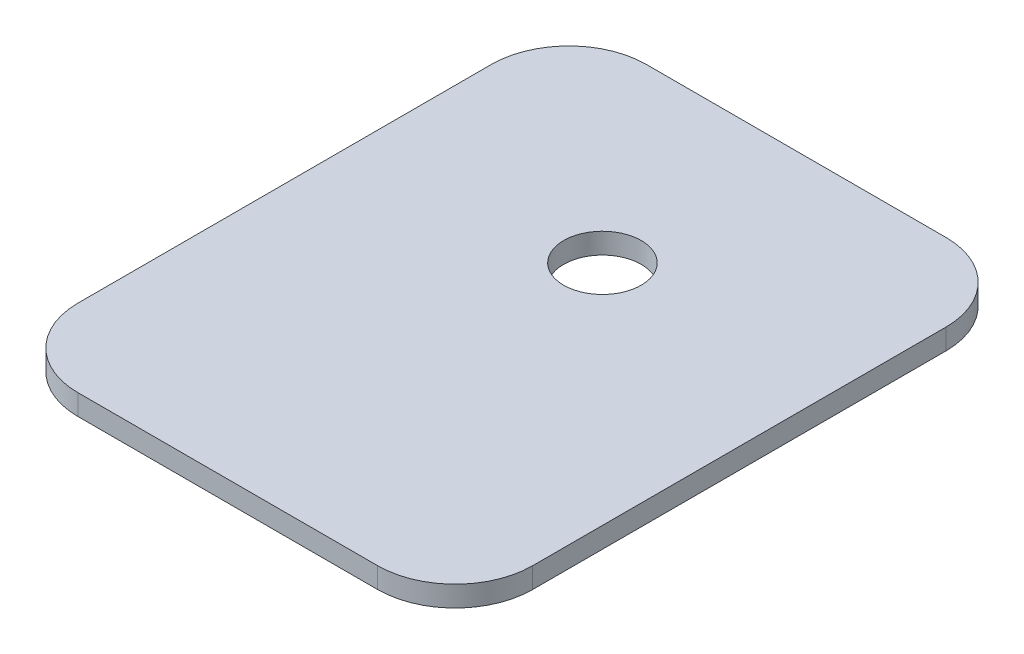
SolidWorks part; units mm, degrees
ref_plane "Front Plane" through (0, 0, 0) normal (0, 0, 1) x (1, 0, 0)
ref_plane "Top Plane" through (0, 0, 0) normal (0, 1, 0) x (1, 0, 0)
ref_plane "Right Plane" through (0, 0, 0) normal (1, 0, 0) x (0, 0, -1)
sketch "Sketch1" plane through (0, 0, 0) normal (0, 1, 0) x (1, 0, 0)
  line L1 (-17.6, -22) -> (17.6, -22)
  line L2 (-17.6, -22) -> (-17.6, 22)
  line L3 (-17.6, 22) -> (17.6, 22)
  line L4 (17.6, -22) -> (17.6, 22)
  line L5 (-17.6, -22) -> (17.6, 22) construction
  line L6 (-17.6, 22) -> (17.6, -22) construction
  point P0 (0, 0)
  dimension "D1" = 35.2
  dimension "D2" = 44
extrude "Boss-Extrude1" add sketch "Sketch1" along normal blind 1.6
fillet "Fillet1" radius 6 4 edges at (-17.6, 0.8, -22) (17.6, 0.8, -22) (-17.6, 0.8, 22) (17.6, 0.8, 22)
sketch "Sketch2" plane through (0, 1.6, 0) normal (0, 1, 0) x (1, 0, 0)
  line L0 (11.6, 22) -> (-11.6, 22) construction
  circle A0 centre (0, 7) radius 3
  dimension "D1" = 6
  dimension "D2" = 15
extrude "Cut-Extrude1" cut sketch "Sketch2" against normal up to surface (1.6 mm away) up to face at (0, 0, 0)
